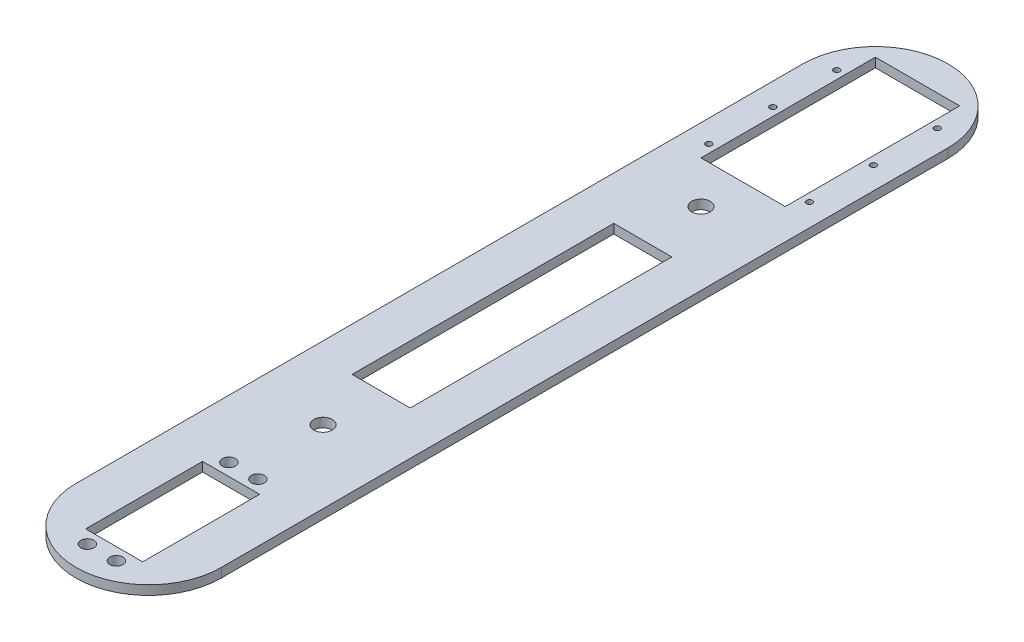
SolidWorks part; units mm, degrees
ref_plane "Front" through (0, 0, 0) normal (0, 0, 1) x (1, 0, 0)
ref_plane "Top" through (0, 0, 0) normal (0, 1, 0) x (1, 0, 0)
ref_plane "Right" through (0, 0, 0) normal (1, 0, 0) x (0, 0, -1)
sketch "Sketch2" plane through (0, 0, 0) normal (0, 1, 0) x (1, 0, 0)
  line L1 (0, 0) -> (50, 0)
  line L2 (0, 0) -> (0, -300)
  line L3 (0, -300) -> (50, -300)
  line L4 (50, 0) -> (50, -300)
  dimension "D1" = 300
  dimension "D2" = 50
extrude "Boss-Extrude1" add sketch "Sketch2" along normal blind 3.175
sketch "Sketch3" plane through (0, 3.175, 0) normal (0, 1, 0) x (1, 0, 0)
  line L0 (25, 0) -> (25, -300) construction
  line L1 (50, 0) -> (0, 0) construction
  line L2 (0, -300) -> (50, -300) construction
  line L3 (0, -150) -> (50, -150) construction
  line L4 (0, 0) -> (0, -300) construction
  line L5 (50, -300) -> (50, 0) construction
  line L6 (34.81, -266.73) -> (15.19, -266.73) construction
  line L7 (10.5, -10.5) -> (39.5, -10.5)
  line L8 (10.5, -10.5) -> (10.5, -70.5)
  line L9 (10.5, -70.5) -> (39.5, -70.5)
  line L10 (39.5, -10.5) -> (39.5, -70.5)
  line L11 (15.19, -246.62) -> (34.81, -246.62)
  line L12 (15.19, -246.62) -> (15.19, -286.84)
  line L13 (15.19, -286.84) -> (34.81, -286.84)
  line L14 (34.81, -246.62) -> (34.81, -286.84)
  circle A0 centre (7.7, -21) radius 1.025
  circle A1 centre (7.7, -43) radius 1.025
  circle A2 centre (7.7, -65) radius 1.025
  circle A3 centre (42.3, -65) radius 1.025
  circle A4 centre (42.3, -43) radius 1.025
  circle A5 centre (42.3, -21) radius 1.025
  circle A6 centre (20, -291.07) radius 2.25
  circle A7 centre (30, -291.07) radius 2.25
  circle A8 centre (20, -242.39) radius 2.25
  circle A9 centre (30, -242.39) radius 2.25
  dimension "D4" = 2.05
  dimension "D5" = 22
  dimension "D6" = 22
  dimension "D7" = 5.5
  dimension "D8" = 2.8
  dimension "D12" = 4.5
  dimension "D13" = 4.23
  dimension "D14" = 5
  dimension "D1" = 60
  dimension "D2" = 10.5
  dimension "D3" = 29
  dimension "D9" = 19.62
  dimension "D10" = 40.22
  dimension "D11" = 13.16
extrude "Cut-Extrude1" cut sketch "Sketch3" against normal blind 6.35
sketch "Sketch4" plane through (0, 3.175, 0) normal (0, 1, 0) x (1, 0, 0)
  line L0 (0, -25) -> (0, 0)
  line L1 (0, 0) -> (50, 0)
  line L2 (50, 0) -> (50, -25)
  line L3 (0, -275) -> (0, -300)
  line L4 (0, -300) -> (50, -300)
  line L5 (50, -300) -> (50, -275)
  circle A0 centre (25, -25) radius 25
  circle A1 centre (25, -275) radius 25
  line M19 (0, 0) -> (0, -300)
  line M20 (0, -300) -> (50, -300)
  line M21 (50, -300) -> (50, 0)
  line M22 (50, 0) -> (0, 0)
extrude "Cut-Extrude2" cut sketch "Sketch4" against normal blind 6.35 contours A0 L1 M19 | A0 M21 M22 | A1 M19 M20 | A1 L4 M21
sketch "Sketch5" plane through (0, 0, 0) normal (0, -1, 0) x (1, 0, 0)
  line L0 (25, 300) -> (25, 0) construction
  line L1 (0, 150) -> (50, 150) construction
  line L2 (0, 25) -> (0, 275) construction
  line L3 (50, 275) -> (50, 25) construction
  line L5 (15, 195) -> (35, 195)
  line L6 (15, 195) -> (15, 105)
  line L7 (15, 105) -> (35, 105)
  line L8 (35, 195) -> (35, 105)
  arc A0 (50, 275) -> (0, 275) centre (25, 275) ccw construction
  arc A1 (0, 25) -> (50, 25) centre (25, 25) ccw construction
  circle A2 centre (25, 215) radius 3.175
  circle A3 centre (25, 85) radius 3.175
  dimension "D3" = 6.35
  dimension "D4" = 65
  dimension "D1" = 20
  dimension "D2" = 90
extrude "Cut-Extrude3" cut sketch "Sketch5" against normal blind 6.35
